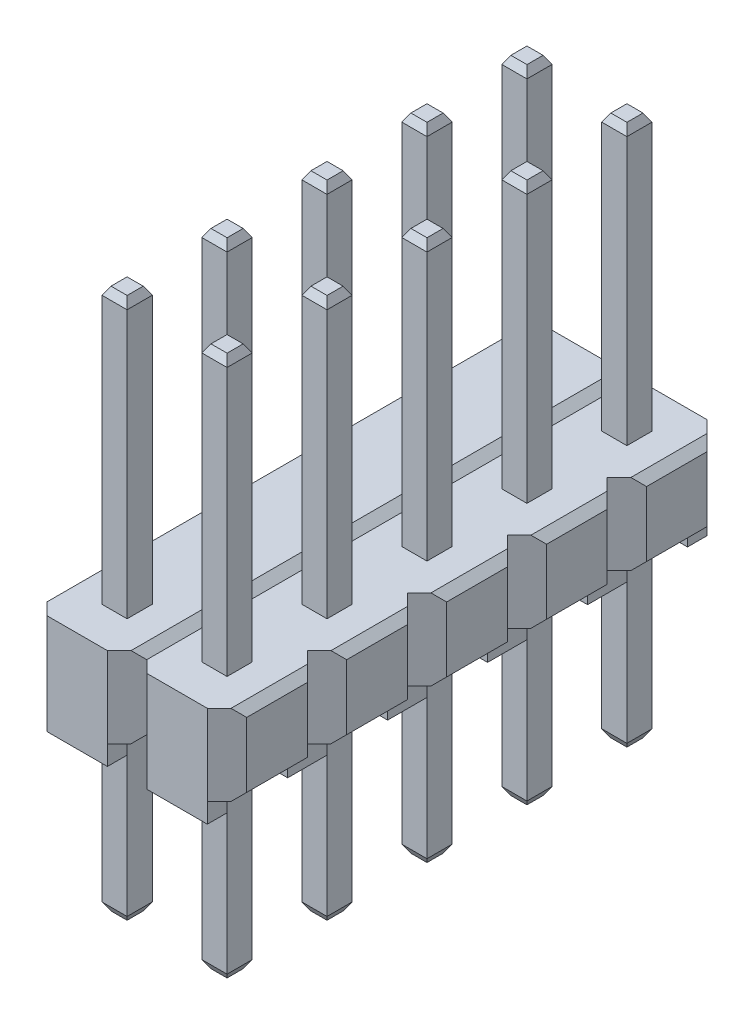
SolidWorks part; units mm, degrees
ref_plane "Front Plane" through (0, 0, 0) normal (0, 0, 1) x (1, 0, 0)
ref_plane "Top Plane" through (0, 0, 0) normal (0, 1, 0) x (1, 0, 0)
ref_plane "Right Plane" through (0, 0, 0) normal (1, 0, 0) x (0, 0, -1)
sketch "Sketch1" plane through (0, 0, 0) normal (0, 1, 0) x (1, 0, 0)
  line L0 (0, 0.77) -> (0.5, 1.27)
  line L1 (0, 4.31) -> (-0.5, 3.81)
  line L2 (2.04, 1.27) -> (2.54, 0.77)
  line L3 (2.54, 0.77) -> (2.54, -0.77)
  line L4 (2.54, -0.77) -> (2.04, -1.27)
  line L5 (-2.54, 0) -> (2.54, 0) construction
  line L6 (0.5, -1.27) -> (0, -0.77)
  line L7 (-2.54, 3.31) -> (-2.04, 3.81)
  line L8 (-1.397, 0) -> (1.397, 0) construction
  line L9 (-2.54, -0.77) -> (-2.54, 0.77)
  line L10 (-1.59, -0.32) -> (-0.95, -0.32)
  line L11 (0.95, -0.32) -> (1.59, -0.32)
  line L12 (0.95, -0.32) -> (0.95, 0.32)
  line L13 (0.95, 0.32) -> (1.59, 0.32)
  line L14 (1.59, -0.32) -> (1.59, 0.32)
  line L15 (-2.54, 0.77) -> (-2.04, 1.27)
  line L16 (-0.95, -0.32) -> (-0.95, 0.32)
  line L17 (-1.59, 0.32) -> (-0.95, 0.32)
  line L18 (0, -0.77) -> (-0.5, -1.27)
  line L19 (-2.04, -1.27) -> (-2.54, -0.77)
  line L20 (-0.5, 3.81) -> (0, 3.31)
  line L21 (-1.59, -0.32) -> (-1.59, 0.32)
  line L22 (1.59, 4.76) -> (1.59, 5.4)
  line L23 (-0.5, 1.27) -> (0, 0.77)
  line L24 (2.04, 3.81) -> (2.54, 3.31)
  line L25 (2.54, 1.77) -> (2.04, 1.27)
  line L26 (0, -3.4925) -> (0, 3.4925) construction
  line L27 (0.95, 2.86) -> (1.59, 2.86)
  line L28 (0.95, 2.22) -> (1.59, 2.22)
  line L29 (-2.54, 1.77) -> (-2.54, 3.31)
  line L30 (-1.59, 2.22) -> (-1.59, 2.86)
  line L31 (-0.95, 2.22) -> (-0.95, 2.86)
  line L32 (0, 1.77) -> (-0.5, 1.27)
  line L35 (2.54, 3.31) -> (2.54, 1.77)
  line L36 (0, 3.31) -> (0.5, 3.81)
  line L37 (0.5, 1.27) -> (0, 1.77)
  line L38 (-1.59, 2.22) -> (-0.95, 2.22)
  line L39 (0.95, 2.22) -> (0.95, 2.86)
  line L40 (1.59, 2.22) -> (1.59, 2.86)
  line L41 (-2.04, 1.27) -> (-2.54, 1.77)
  line L42 (-1.59, 2.86) -> (-0.95, 2.86)
  line L43 (0, -4.31) -> (0.5, -3.81)
  line L44 (-2.04, 6.35) -> (-0.5, 6.35)
  line L45 (-0.5, 6.35) -> (0, 5.85)
  line L46 (-1.59, 4.76) -> (-1.59, 5.4)
  line L47 (0.95, 4.76) -> (1.59, 4.76)
  line L48 (2.54, 5.85) -> (2.54, 4.31)
  line L49 (-2.04, 3.81) -> (-2.54, 4.31)
  line L50 (2.04, -3.81) -> (2.54, -4.31)
  line L51 (-1.59, 4.76) -> (-0.95, 4.76)
  line L52 (2.54, -4.31) -> (2.54, -5.85)
  line L53 (0, 5.85) -> (0.5, 6.35)
  line L54 (2.54, 4.31) -> (2.04, 3.81)
  line L55 (2.04, 6.35) -> (2.54, 5.85)
  line L56 (0.95, 5.4) -> (1.59, 5.4)
  line L57 (-2.54, 5.85) -> (-2.04, 6.35)
  line L58 (-2.54, 4.31) -> (-2.54, 5.85)
  line L59 (-1.59, 5.4) -> (-0.95, 5.4)
  line L60 (-0.95, 4.76) -> (-0.95, 5.4)
  line L61 (0.5, 3.81) -> (0, 4.31)
  line L62 (0.5, 6.35) -> (2.04, 6.35)
  line L63 (0.95, 4.76) -> (0.95, 5.4)
  line L64 (2.54, -5.85) -> (2.04, -6.35)
  line L65 (2.04, -6.35) -> (0.5, -6.35)
  line L66 (0.5, -6.35) -> (0, -5.85)
  line L67 (-2.54, -1.77) -> (-2.04, -1.27)
  line L68 (-0.5, -6.35) -> (-2.04, -6.35)
  line L69 (-2.54, -5.85) -> (-2.54, -4.31)
  line L70 (-1.59, -5.4) -> (-0.95, -5.4)
  line L71 (0.95, -5.4) -> (1.59, -5.4)
  line L72 (0.95, -5.4) -> (0.95, -4.76)
  line L73 (0.95, -4.76) -> (1.59, -4.76)
  line L74 (1.59, -5.4) -> (1.59, -4.76)
  line L75 (-2.54, -4.31) -> (-2.04, -3.81)
  line L76 (-0.95, -5.4) -> (-0.95, -4.76)
  line L77 (-1.59, -4.76) -> (-0.95, -4.76)
  line L78 (0, -5.85) -> (-0.5, -6.35)
  line L79 (-2.04, -6.35) -> (-2.54, -5.85)
  line L80 (-0.5, -1.27) -> (0, -1.77)
  line L81 (-1.59, -5.4) -> (-1.59, -4.76)
  line L82 (-0.5, -3.81) -> (0, -4.31)
  line L83 (2.04, -1.27) -> (2.54, -1.77)
  line L84 (2.54, -3.31) -> (2.04, -3.81)
  line L86 (0.95, -2.22) -> (1.59, -2.22)
  line L87 (0.95, -2.86) -> (1.59, -2.86)
  line L88 (-2.54, -3.31) -> (-2.54, -1.77)
  line L89 (-1.59, -2.86) -> (-1.59, -2.22)
  line L90 (-0.95, -2.86) -> (-0.95, -2.22)
  line L91 (0, -3.31) -> (-0.5, -3.81)
  line L92 (2.54, -1.77) -> (2.54, -3.31)
  line L93 (0, -1.77) -> (0.5, -1.27)
  line L94 (0.5, -3.81) -> (0, -3.31)
  line L95 (-1.59, -2.86) -> (-0.95, -2.86)
  line L96 (0.95, -2.86) -> (0.95, -2.22)
  line L97 (1.59, -2.86) -> (1.59, -2.22)
  line L98 (-2.04, -3.81) -> (-2.54, -3.31)
  line L99 (-1.59, -2.22) -> (-0.95, -2.22)
  dimension "D1" = 12.7
  dimension "D2" = 6.35
  dimension "D3" = 5.08
  dimension "D4" = 2.54
  dimension "D5" = 2.54
extrude "Boss-Extrude1" add sketch "Sketch1" against normal blind 2.05
sketch "Sketch2" plane through (0, 0, 0) normal (0, 0, 1) x (1, 0, 0)
  line L0 (-2.54, -0.2) -> (-2.34, 0)
  line L1 (-2.54, -2.05) -> (-2.54, 0) construction
  line L2 (-2.54, 0) -> (-2.04, 0) construction
  line L3 (-2.34, 0) -> (-2.54, 0)
  line L4 (-2.54, 0) -> (-2.54, -0.2)
  line L5 (-0.2, 0) -> (0.2, 0)
  line L6 (-0.5, 0) -> (0, 0) construction
  line L7 (0, 0) -> (0.5, 0) construction
  line L8 (0.2, 0) -> (0, -0.2)
  line L9 (0, -2.05) -> (0, 0) construction
  line L10 (0, -0.2) -> (-0.2, 0)
  line L11 (2.54, 0) -> (2.34, 0)
  line L12 (2.04, 0) -> (2.54, 0) construction
  line L13 (2.34, 0) -> (2.54, -0.2)
  line L14 (2.54, -2.05) -> (2.54, 0) construction
  line L15 (2.54, -0.2) -> (2.54, 0)
  line L16 (-2.54, -1.025) -> (2.54, -1.025) construction
  line L17 (2.54, -1.85) -> (2.54, -2.05)
  line L18 (2.34, -2.05) -> (2.54, -1.85)
  line L19 (2.54, -2.05) -> (2.34, -2.05)
  line L20 (0, -1.85) -> (-0.2, -2.05)
  line L21 (0.2, -2.05) -> (0, -1.85)
  line L22 (-0.2, -2.05) -> (0.2, -2.05)
  line L23 (-2.54, -2.05) -> (-2.54, -1.85)
  line L24 (-2.34, -2.05) -> (-2.54, -2.05)
  line L25 (-2.54, -1.85) -> (-2.34, -2.05)
  dimension "D1" = 0.2
extrude "Cut-Extrude1" cut sketch "Sketch2" against normal mid plane 20
sketch "Sketch3" plane through (0, -2.05, 0) normal (0, -1, 0) x (1, 0, 0)
  line L0 (2.04, -6.35) -> (0.5, -6.35) construction
  line L1 (-2.04, 6.35) -> (-0.5, 6.35)
  line L2 (-2.04, 6.35) -> (-2.04, 5.85)
  line L3 (-2.04, 5.85) -> (-0.5, 5.85)
  line L4 (-0.5, 6.35) -> (-0.5, 5.85)
  line L5 (0.5, 6.35) -> (2.04, 6.35)
  line L6 (0.5, 6.35) -> (0.5, 5.85)
  line L7 (0.5, 5.85) -> (2.04, 5.85)
  line L8 (2.04, 6.35) -> (2.04, 5.85)
  line L9 (-2.04, -0.77) -> (-0.5, -0.77)
  line L10 (-2.04, -0.77) -> (-2.04, -1.77)
  line L11 (-2.04, -1.77) -> (-0.5, -1.77)
  line L12 (-0.5, -0.77) -> (-0.5, -1.77)
  line L13 (0.5, -0.77) -> (2.04, -0.77)
  line L14 (0.5, -0.77) -> (0.5, -1.77)
  line L15 (0.5, -1.77) -> (2.04, -1.77)
  line L16 (2.04, -0.77) -> (2.04, -1.77)
  line L17 (-2.04, -3.31) -> (-0.5, -3.31)
  line L18 (-2.04, -3.31) -> (-2.04, -4.31)
  line L19 (-2.04, -4.31) -> (-0.5, -4.31)
  line L20 (-0.5, -3.31) -> (-0.5, -4.31)
  line L21 (0.5, -3.31) -> (2.04, -3.31)
  line L22 (0.5, -3.31) -> (0.5, -4.31)
  line L23 (0.5, -4.31) -> (2.04, -4.31)
  line L24 (2.04, -3.31) -> (2.04, -4.31)
  line L25 (-2.04, -6.35) -> (-0.5, -6.35)
  line L26 (-2.04, -6.35) -> (-2.04, -5.85)
  line L27 (-2.04, -5.85) -> (-0.5, -5.85)
  line L28 (-0.5, -6.35) -> (-0.5, -5.85)
  line L29 (0.5, -6.35) -> (2.04, -6.35)
  line L30 (0.5, -6.35) -> (0.5, -5.85)
  line L31 (0.5, -5.85) -> (2.04, -5.85)
  line L32 (2.04, -6.35) -> (2.04, -5.85)
  line L34 (-2.04, 4.31) -> (-0.5, 4.31)
  line L35 (-2.04, 4.31) -> (-2.04, 3.31)
  line L36 (-2.04, 3.31) -> (-0.5, 3.31)
  line L37 (-0.5, 4.31) -> (-0.5, 3.31)
  line L38 (-2.04, 1.77) -> (-0.5, 1.77)
  line L39 (-2.04, 1.77) -> (-2.04, 0.77)
  line L40 (-2.04, 0.77) -> (-0.5, 0.77)
  line L41 (-0.5, 1.77) -> (-0.5, 0.77)
  line L42 (0.5, 4.31) -> (2.04, 4.31)
  line L43 (0.5, 4.31) -> (0.5, 3.31)
  line L44 (0.5, 3.31) -> (2.04, 3.31)
  line L45 (2.04, 4.31) -> (2.04, 3.31)
  line L46 (0.5, 1.77) -> (2.04, 1.77)
  line L47 (0.5, 1.77) -> (0.5, 0.77)
  line L48 (0.5, 0.77) -> (2.04, 0.77)
  line L49 (2.04, 1.77) -> (2.04, 0.77)
  dimension "D1" = 0.5
  dimension "D2" = 1
extrude "Boss-Extrude2" add sketch "Sketch3" along normal blind 0.5
sketch "Sketch4" plane through (0, 0, 0) normal (0, 1, 0) x (1, 0, 0)
  line L1 (-1.59, 5.4) -> (-0.95, 5.4)
  line L2 (-1.59, 5.4) -> (-1.59, 4.76)
  line L3 (-1.59, 4.76) -> (-0.95, 4.76)
  line L4 (-0.95, 5.4) -> (-0.95, 4.76)
  line L5 (0.95, 5.4) -> (1.59, 5.4)
  line L6 (0.95, 5.4) -> (0.95, 4.76)
  line L7 (0.95, 4.76) -> (1.59, 4.76)
  line L8 (1.59, 5.4) -> (1.59, 4.76)
  line L9 (-1.59, 2.86) -> (-0.95, 2.86)
  line L10 (-1.59, 2.86) -> (-1.59, 2.22)
  line L11 (-1.59, 2.22) -> (-0.95, 2.22)
  line L12 (-0.95, 2.86) -> (-0.95, 2.22)
  line L13 (0.95, 2.86) -> (1.59, 2.86)
  line L14 (0.95, 2.86) -> (0.95, 2.22)
  line L15 (0.95, 2.22) -> (1.59, 2.22)
  line L16 (1.59, 2.86) -> (1.59, 2.22)
  line L17 (-1.59, 0.32) -> (-0.95, 0.32)
  line L18 (-1.59, 0.32) -> (-1.59, -0.32)
  line L19 (-1.59, -0.32) -> (-0.95, -0.32)
  line L20 (-0.95, 0.32) -> (-0.95, -0.32)
  line L21 (0.95, 0.32) -> (1.59, 0.32)
  line L22 (0.95, 0.32) -> (0.95, -0.32)
  line L23 (0.95, -0.32) -> (1.59, -0.32)
  line L24 (1.59, 0.32) -> (1.59, -0.32)
  line L25 (-1.59, -2.22) -> (-0.95, -2.22)
  line L26 (-1.59, -2.22) -> (-1.59, -2.86)
  line L27 (-1.59, -2.86) -> (-0.95, -2.86)
  line L28 (-0.95, -2.22) -> (-0.95, -2.86)
  line L29 (0.95, -2.22) -> (1.59, -2.22)
  line L30 (0.95, -2.22) -> (0.95, -2.86)
  line L31 (0.95, -2.86) -> (1.59, -2.86)
  line L32 (1.59, -2.22) -> (1.59, -2.86)
  line L33 (-1.59, -4.76) -> (-0.95, -4.76)
  line L34 (-1.59, -4.76) -> (-1.59, -5.4)
  line L35 (-1.59, -5.4) -> (-0.95, -5.4)
  line L36 (-0.95, -4.76) -> (-0.95, -5.4)
  line L37 (0.95, -4.76) -> (1.59, -4.76)
  line L38 (0.95, -4.76) -> (0.95, -5.4)
  line L39 (0.95, -5.4) -> (1.59, -5.4)
  line L40 (1.59, -4.76) -> (1.59, -5.4)
extrude "Boss-Extrude3" add sketch "Sketch4" along normal blind 7 and the other way offset from surface (6.75 mm away) 4.7 other way up to face at (-1.27, -2.05, -2.54)
chamfer "Chamfer1" distance 0.2 angle 30 80 edges at (-1.27, -6.75, 0.32) (-0.95, -6.75, 0) (-1.27, -6.75, -0.32) (-1.59, -6.75, 0) (-1.27, -6.75, -2.22) (-0.95, -6.75, -2.54) (-1.27, -6.75, -2.86) (-1.59, -6.75, -2.54) (-1.27, -6.75, -4.76) (-0.95, -6.75, -5.08) (-1.27, -6.75, -5.4) (-1.59, -6.75, -5.08) (1.27, -6.75, 0.32) (1.59, -6.75, 0) (1.27, -6.75, -0.32) (0.95, -6.75, 0) (1.27, -6.75, -2.22) (1.59, -6.75, -2.54) (1.27, -6.75, -2.86) (0.95, -6.75, -2.54) (1.27, -6.75, -4.76) (1.59, -6.75, -5.08) (1.27, -6.75, -5.4) (0.95, -6.75, -5.08) (-1.27, 7, -0.32) (-0.95, 7, 0) (-1.27, 7, 0.32) (-1.59, 7, 0) (-1.27, 7, -2.86) (-0.95, 7, -2.54) (-1.27, 7, -2.22) (-1.59, 7, -2.54) (-1.27, 7, -5.4) (-0.95, 7, -5.08) (-1.27, 7, -4.76) (-1.59, 7, -5.08) (1.27, 7, -0.32) (1.59, 7, 0) (1.27, 7, 0.32) (0.95, 7, 0) (1.27, 7, -2.86) (1.59, 7, -2.54) (1.27, 7, -2.22) (0.95, 7, -2.54) (1.27, 7, -5.4) (1.59, 7, -5.08) (1.27, 7, -4.76) (0.95, 7, -5.08) (1.27, -6.75, 2.86) (1.59, -6.75, 2.54) (1.27, -6.75, 2.22) (0.95, -6.75, 2.54) (-1.27, -6.75, 2.86) (-0.95, -6.75, 2.54) (-1.27, -6.75, 2.22) (-1.59, -6.75, 2.54) (-1.27, -6.75, 5.4) (-0.95, -6.75, 5.08) (-1.27, -6.75, 4.76) (-1.59, -6.75, 5.08) (1.27, -6.75, 5.4) (1.59, -6.75, 5.08) (1.27, -6.75, 4.76) (0.95, -6.75, 5.08) (1.27, 7, 4.76) (1.59, 7, 5.08) (1.27, 7, 5.4) (0.95, 7, 5.08) (-1.27, 7, 4.76) (-0.95, 7, 5.08) (-1.27, 7, 5.4) (-1.59, 7, 5.08) (1.27, 7, 2.22) (1.59, 7, 2.54) (1.27, 7, 2.86) (0.95, 7, 2.54) (-1.27, 7, 2.22) (-0.95, 7, 2.54) (-1.27, 7, 2.86) (-1.59, 7, 2.54)
sketch "Sketch5" plane through (0, -6.75, 0) normal (0, -1, 0) x (1, 0, 0)
  line L0 (-1.4745, -4.8755) -> (-1.0655, -5.2845) construction
  line L1 (-1.0655, -5.2845) -> (-1.0655, -4.8755) construction
  line L2 (-1.0655, -4.8755) -> (-1.4745, -5.2845) construction
  line L3 (-1.4745, 5.2845) -> (-1.0655, 4.8755) construction
  line L4 (-1.0655, 4.8755) -> (-1.0655, 5.2845) construction
  line L5 (-1.0655, 5.2845) -> (-1.4745, 4.8755) construction
  line L6 (-1.4745, 4.8755) -> (-1.0655, 4.8755) construction
  circle A0 centre (-1.27, -5.08) radius 0.125
  circle A1 centre (-1.27, 5.08) radius 0.125
  dimension "D1" = 0.25
extrude "Cut-Extrude2" cut sketch "Sketch5" against normal blind 1
scale "Scale1" scale about centroid uniform scaling yes scale factor 0.5
